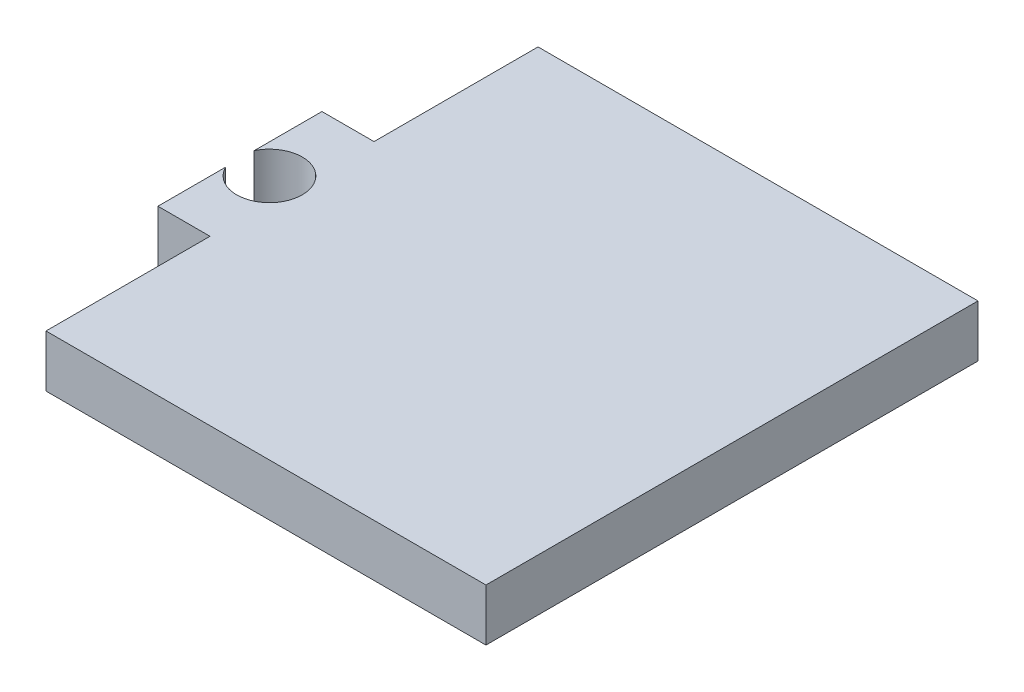
SolidWorks part; units mm, degrees
ref_plane "Front Plane" through (0, 0, 0) normal (0, 0, 1) x (1, 0, 0)
ref_plane "Top Plane" through (0, 0, 0) normal (0, 1, 0) x (1, 0, 0)
ref_plane "Right Plane" through (0, 0, 0) normal (1, 0, 0) x (0, 0, -1)
sketch "Sketch1" plane through (0, 0, 0) normal (0, 1, 0) x (1, 0, 0)
  line L0 (0, 15.8718) -> (0, 20)
  line L1 (3.175, 0) -> (30, 0)
  line L2 (0, 10) -> (0, 14.1282)
  line L3 (3.175, 30) -> (30, 30)
  line L4 (30, 0) -> (30, 30)
  line L7 (0, 20) -> (3.175, 20)
  line L8 (3.175, 30) -> (3.175, 20)
  line L11 (0, 10) -> (3.175, 10)
  line L12 (3.175, 0) -> (3.175, 10)
  arc A0 (0, 14.1282) -> (0, 15.8718) centre (1.8, 15) ccw
  dimension "D1" = 4
  dimension "D2" = 1.8
  dimension "D3" = 3.175
  dimension "D4" = 10
  dimension "D5" = 10
  dimension "D6" = 5
extrude "Boss-Extrude1" add sketch "Sketch1" along normal blind 3.175 contours L8 L7 L0 A0 L2 L11 L12 L1 L4 L3
